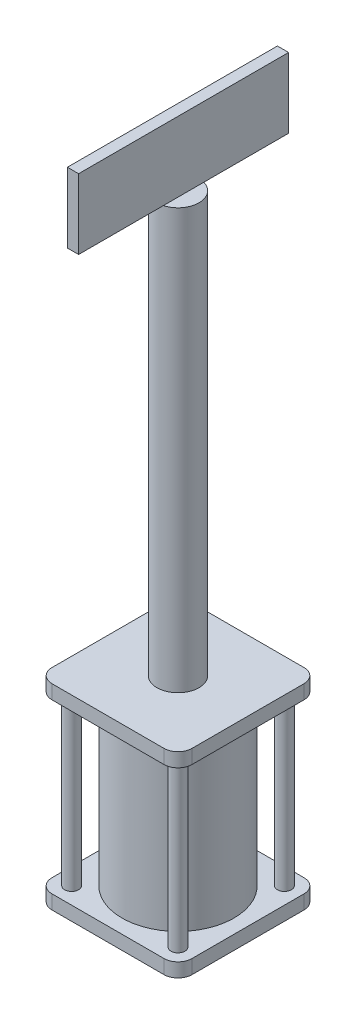
SolidWorks part; units mm, degrees
ref_plane "Front Plane" through (0, 0, 0) normal (0, 0, 1) x (1, 0, 0)
ref_plane "Top Plane" through (0, 0, 0) normal (0, 1, 0) x (1, 0, 0)
ref_plane "Right Plane" through (0, 0, 0) normal (1, 0, 0) x (0, 0, -1)
sketch "Sketch1" plane through (0, 0, 0) normal (0, 1, 0) x (1, 0, 0)
  line L1 (-50, -50) -> (50, -50)
  line L2 (-50, -50) -> (-50, 50)
  line L3 (-50, 50) -> (50, 50)
  line L4 (50, -50) -> (50, 50)
  line L5 (-50, -50) -> (50, 50) construction
  line L6 (-50, 50) -> (50, -50) construction
  point P0 (0, 0)
  dimension "D1" = 100
  dimension "D2" = 100
extrude "Boss-Extrude1" add sketch "Sketch1" along normal blind 10
sketch "Sketch2" plane through (0, 10, 0) normal (0, 1, 0) x (1, 0, 0)
  circle A0 centre (0, 0) radius 40
  dimension "D1" = 80
extrude "Boss-Extrude2" add sketch "Sketch2" along normal blind 120 separate body
sketch "Sketch3" plane through (0, 130, 0) normal (0, 1, 0) x (1, 0, 0)
  line L1 (-50, 50) -> (50, 50)
  line L2 (-50, 50) -> (-50, -50)
  line L3 (-50, -50) -> (50, -50)
  line L4 (50, 50) -> (50, -50)
extrude "Boss-Extrude3" add sketch "Sketch3" along normal blind 10 separate body
sketch "Sketch4" plane through (0, 140, 0) normal (0, 1, 0) x (1, 0, 0)
  circle A0 centre (0, 0) radius 15
  dimension "D1" = 30
extrude "Boss-Extrude4" add sketch "Sketch4" along normal blind 300 separate body
sketch "Sketch5" plane through (0, 10, 0) normal (0, 1, 0) x (1, 0, 0)
  line L0 (-50, 50) -> (-50, -50) construction
  line L1 (50, 50) -> (-50, 50) construction
  line L2 (0, 50) -> (0, 0) construction
  line L3 (0, 0) -> (50, 0) construction
  line L4 (50, -50) -> (50, 50) construction
  circle A0 centre (-38, 38) radius 5
  circle A1 centre (38, 38) radius 5
  circle A2 centre (38, -38) radius 5
  circle A3 centre (-38, -38) radius 5
  dimension "D1" = 10
  dimension "D2" = 12
  dimension "D3" = 12
extrude "Boss-Extrude5" add sketch "Sketch5" along normal up to surface (120 mm away) up to face at (0, 130, 0)
fillet "Fillet1" radius 10 8 edges at (50, 5, -50) (50, 5, 50) (-50, 5, 50) (-50, 5, -50) (-50, 135, -50) (50, 135, -50) (50, 135, 50) (-50, 135, 50)
sketch "Sketch6" plane through (0, 440, 0) normal (0, 1, 0) x (1, 0, 0)
  line L1 (-4, -75) -> (4, -75)
  line L2 (-4, -75) -> (-4, 75)
  line L3 (-4, 75) -> (4, 75)
  line L4 (4, -75) -> (4, 75)
  line L5 (-4, -75) -> (4, 75) construction
  line L6 (-4, 75) -> (4, -75) construction
  point P0 (0, 0)
  dimension "D1" = 150
  dimension "D2" = 8
extrude "Boss-Extrude6" add sketch "Sketch6" along normal blind 50 separate body
